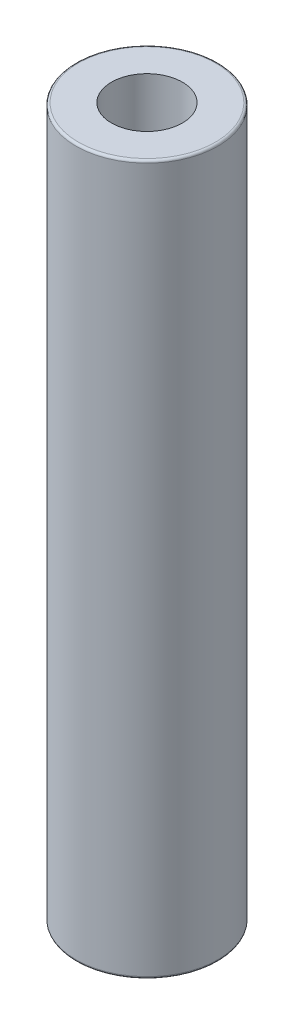
SolidWorks part; units mm, degrees
ref_plane "正面" through (0, 0, 0) normal (0, 0, 1) x (1, 0, 0)
ref_plane "平面" through (0, 0, 0) normal (0, 1, 0) x (1, 0, 0)
ref_plane "右側面" through (0, 0, 0) normal (1, 0, 0) x (0, 0, -1)
sketch "ｽｹｯﾁ1" plane through (0, 0, 0) normal (0, 1, 0) x (1, 0, 0)
  circle A0 centre (0, 0) radius 3
  circle A1 centre (0, 0) radius 1.5
  dimension "D1" = 3
  dimension "D2" = 6
extrude "ﾎﾞｽ - 押し出し1" add sketch "ｽｹｯﾁ1" along normal blind 30
fillet "ﾌｨﾚｯﾄ1" radius 0.1 2 edges at (0, 0, 3) (0, 30, 3)
